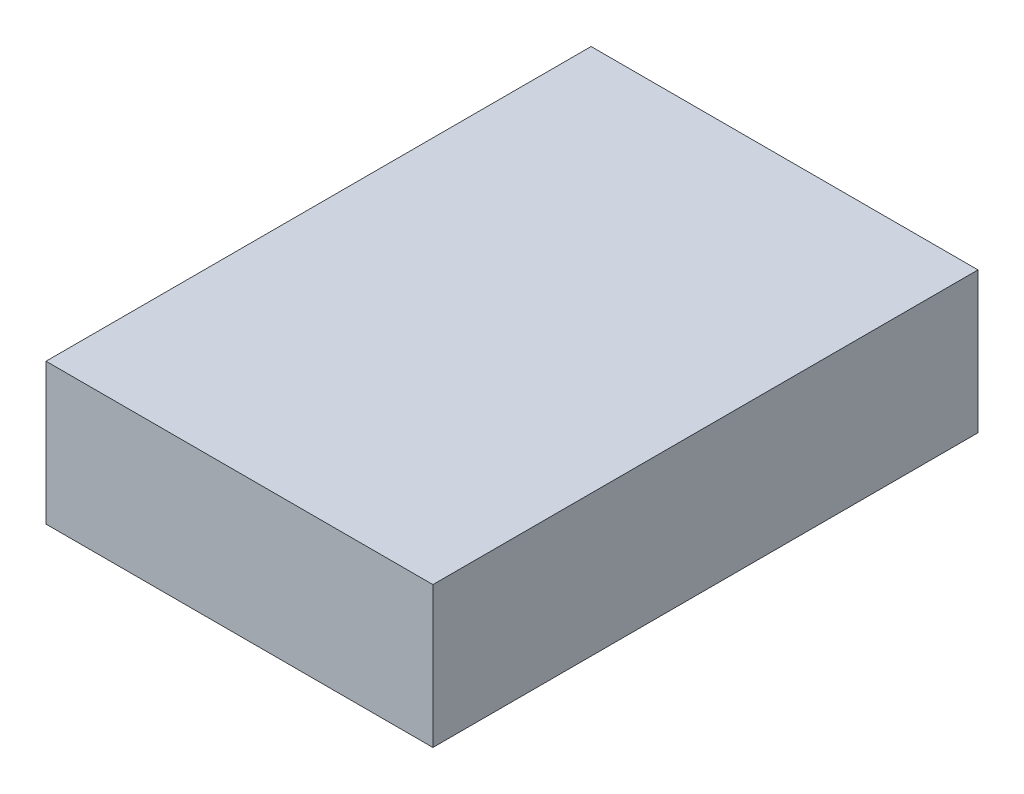
SolidWorks part; units mm, degrees
material "1060 Alloy"
ref_plane "Front" through (0, 0, 0) normal (0, 0, 1) x (1, 0, 0)
ref_plane "Top" through (0, 0, 0) normal (0, 1, 0) x (1, 0, 0)
ref_plane "Right" through (0, 0, 0) normal (1, 0, 0) x (0, 0, -1)
sketch "Sketch1" plane through (0, 0, 0) normal (0, 0, 1) x (1, 0, 0)
  line L1 (0, 0) -> (45.974, 0)
  line L2 (0, 0) -> (0, 16.764)
  line L3 (0, 16.764) -> (45.974, 16.764)
  line L4 (45.974, 0) -> (45.974, 16.764)
  dimension "D1" = 16.764
  dimension "D2" = 45.974
extrude "Boss-Extrude1" add sketch "Sketch1" along normal blind 64.77 contours L3 L4 L1 L2
